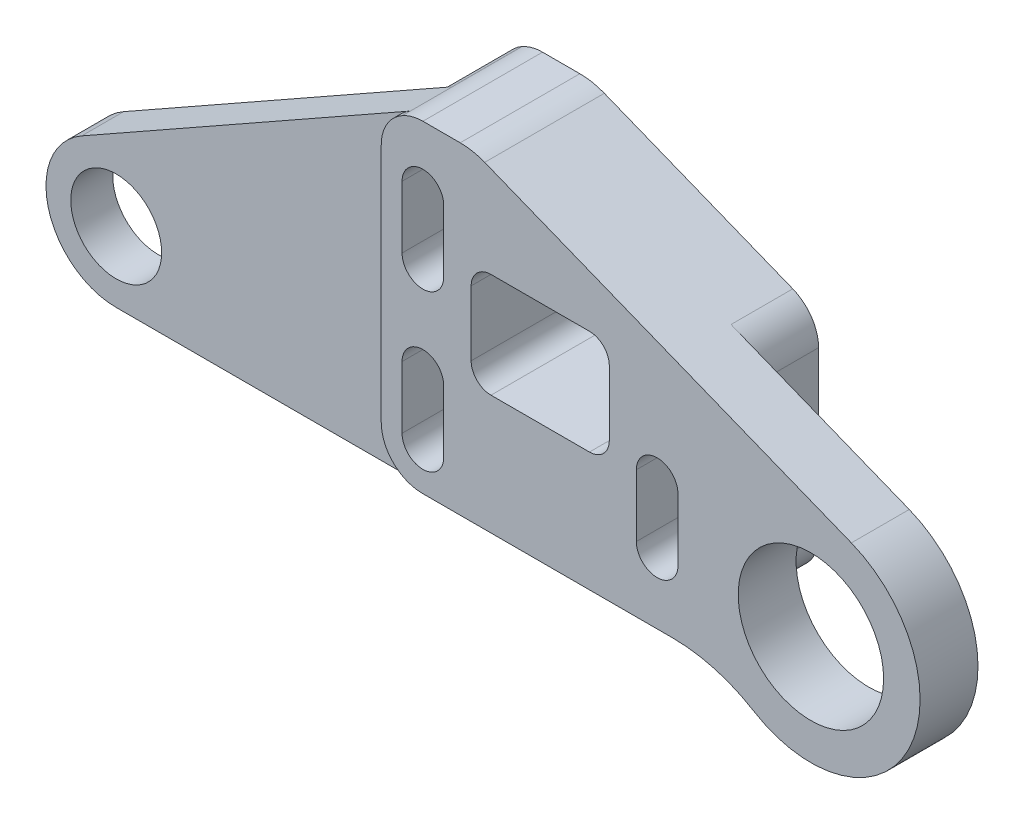
SolidWorks part; units mm, degrees
ref_plane "Plane1" through (0, 0, 0) normal (0, 0, 1) x (1, 0, 0)
ref_plane "Plane2" through (0, 0, 0) normal (0, 1, 0) x (1, 0, 0)
ref_plane "Plane3" through (0, 0, 0) normal (1, 0, 0) x (0, 0, -1)
sketch "Sketch1" plane through (0, 0, 0) normal (0, 0, 1) x (1, 0, 0)
  line L0 (67.6222, 48.4886) -> (60.452, 48.4886)
  line L1 (56.5136, 47.4522) -> (-6.639, 11.7403)
  line L2 (0, -13.4874) -> (108.3963, -13.4874)
  line L3 (142.7734, 19.4876) -> (72.3271, 47.5849)
  arc A0 (-6.639, 11.7403) -> (0, -13.4874) centre (0, 0) ccw
  arc A1 (124.0515, -17.8965) -> (108.3963, -13.4874) centre (108.3963, -43.4848) ccw
  arc A2 (124.0515, -17.8965) -> (142.7734, 19.4876) centre (135.0009, 0.0001) ccw
  arc A3 (72.3271, 47.5849) -> (67.6222, 48.4886) centre (67.6222, 35.7886) ccw
  arc A4 (60.452, 48.4886) -> (56.5136, 47.4522) centre (60.452, 40.4876) ccw
extrude "Base-Extrude" add sketch "Sketch1" along normal blind 22.987
sketch "Sketch2" plane through (0, 0, 22.987) normal (0, 0, 1) x (1, 0, 0)
  line L0 (52.451, 40.5617) -> (52.451, -5.6134)
  line L2 (56.5136, 52.1592) -> (-22.1734, 52.1592)
  line L3 (56.5136, 47.4522) -> (-6.639, 11.7403) construction
  line L4 (56.5136, 47.4522) -> (56.4491, 47.4157)
  line L5 (56.5136, 47.4522) -> (56.5136, 52.1592)
  line L6 (60.325, -13.4874) -> (60.325, -28.1506)
  line L7 (-22.1734, 52.1592) -> (-23.4863, -28.1506)
  line L8 (-23.4863, -28.1506) -> (60.325, -28.1506)
  arc A0 (-6.639, 11.7403) -> (0, -13.4874) centre (0, 0) ccw construction
  arc A1 (60.325, -13.4874) -> (52.451, -5.6134) centre (60.325, -5.6134) cw
  arc A2 (56.4491, 47.4157) -> (52.451, 40.5617) centre (60.325, 40.5617) ccw
  dimension "D2" = 7.874
  dimension "D3" = 7.874
  dimension "D1" = 52.451
extrude "Cut-Extrude1" cut sketch "Sketch2" against normal blind 1.524
sketch "Sketch3" plane through (0, 0, 0) normal (0, 0, -1) x (-1, 0, 0)
  line L0 (-52.451, 40.5617) -> (-52.451, -5.6134) construction
  line L1 (-52.451, 40.5617) -> (-52.451, -5.6134)
  line L2 (-56.4491, 47.4157) -> (-56.4491, 62.4376)
  line L3 (-60.325, -13.4874) -> (-60.325, -35.5857)
  line L4 (-60.325, -35.5857) -> (18.4619, -35.5857)
  line L5 (18.4619, -35.5857) -> (18.4619, 62.4376)
  line L6 (18.4619, 62.4376) -> (-56.4491, 62.4376)
  arc A0 (-60.325, -13.4874) -> (-52.451, -5.6134) centre (-60.325, -5.6134) ccw construction
  arc A1 (-60.325, -13.4874) -> (-52.451, -5.6134) centre (-60.325, -5.6134) ccw
  arc A2 (-52.451, 40.5617) -> (-56.4491, 47.4157) centre (-60.325, 40.5617) ccw construction
  arc A3 (-52.451, 40.5617) -> (-56.4491, 47.4157) centre (-60.325, 40.5617) ccw
extrude "Cut-Extrude2" cut sketch "Sketch3" against normal blind 13.3858
sketch "Sketch4" plane through (0, 0, 0) normal (0, 0, -1) x (-1, 0, 0)
  line L0 (-113.4872, -5.6134) -> (-113.4872, 25.8317)
  line L5 (-108.5303, 33.1454) -> (-119.3461, 60.2632)
  line L6 (-105.6132, -13.4874) -> (-105.6132, -25.7396)
  line L7 (-105.6132, -25.7396) -> (-162.925, -25.7396)
  line L8 (-162.925, -25.7396) -> (-162.925, 60.2632)
  line L9 (-162.925, 60.2632) -> (-119.3461, 60.2632)
  arc A0 (0, -13.4874) -> (6.639, 11.7403) centre (0, 0) ccw construction
  arc A1 (-113.4872, 25.8317) -> (-108.5303, 33.1454) centre (-105.6132, 25.8317) cw
  arc A2 (-105.6132, -13.4874) -> (-113.4872, -5.6134) centre (-105.6132, -5.6134) cw
  dimension "D2" = 7.874
  dimension "D3" = 7.874
  dimension "D1" = 113.4872
extrude "Cut-Extrude3" cut sketch "Sketch4" against normal blind 11.8618
sketch "Sketch5" plane through (0, 0, 21.463) normal (0, 0, 1) x (1, 0, 0)
  circle A0 centre (0, 0) radius 8.7313
  dimension "D1" = 17.4625
extrude "Cut-Extrude4" cut sketch "Sketch5" against normal through all
sketch "Sketch6" plane through (0, 0, 22.987) normal (0, 0, 1) x (1, 0, 0)
  circle A0 centre (135.0009, 0.0001) radius 13.97
  dimension "D1" = 27.94
extrude "Cut-Extrude5" cut sketch "Sketch6" against normal through all
sketch "Sketch7" plane through (0, 0, 22.987) normal (0, 0, 1) x (1, 0, 0)
  line L0 (60.452, 58.42) -> (60.452, -33.02) construction
  line L1 (60.325, -13.4874) -> (108.3963, -13.4874) construction
  line L2 (60.325, -13.4874) -> (0, -13.4874) construction
  line L3 (64.4525, -5.4356) -> (64.4525, 6.5024)
  line L4 (64.4525, 24.5618) -> (64.4525, 36.4998)
  line L5 (56.4515, 36.4998) -> (56.4515, 24.5618)
  line L6 (56.4515, 6.5024) -> (56.4515, -5.4356)
  line L7 (105.4608, 43.18) -> (105.4608, -45.0596) construction
  line L8 (101.4603, 10.9982) -> (101.4603, -0.9398)
  line L9 (73.533, 29.5402) -> (92.456, 29.5402)
  line L10 (69.723, 25.7302) -> (69.723, 13.2588)
  line L11 (92.456, 9.4488) -> (73.533, 9.4488)
  line L12 (96.266, 13.2588) -> (96.266, 25.7302)
  line L13 (109.4613, 10.9982) -> (109.4613, -0.9398)
  circle A0 centre (0, 0) radius 8.7313 construction
  arc A1 (64.4525, 36.4998) -> (56.4515, 36.4998) centre (60.452, 36.4998) ccw
  arc A2 (56.4515, 24.5618) -> (64.4525, 24.5618) centre (60.452, 24.5618) ccw
  arc A3 (64.4525, 6.5024) -> (56.4515, 6.5024) centre (60.452, 6.5024) ccw
  arc A4 (56.4515, -5.4356) -> (64.4525, -5.4356) centre (60.452, -5.4356) ccw
  arc A5 (101.4603, -0.9398) -> (109.4613, -0.9398) centre (105.4608, -0.9398) ccw
  arc A6 (109.4613, 10.9982) -> (101.4603, 10.9982) centre (105.4608, 10.9982) ccw
  arc A7 (69.723, 25.7302) -> (73.533, 29.5402) centre (73.533, 25.7302) cw
  arc A8 (73.533, 9.4488) -> (69.723, 13.2588) centre (73.533, 13.2588) cw
  arc A9 (96.266, 13.2588) -> (92.456, 9.4488) centre (92.456, 13.2588) cw
  arc A10 (92.456, 29.5402) -> (96.266, 25.7302) centre (92.456, 25.7302) cw
  dimension "D2" = 8.001
  dimension "D7" = 105.4608
  dimension "D8" = 69.723
  dimension "D12" = 8.001
  dimension "D13" = 8.001
  dimension "D11" = 3.81
  dimension "D9" = 3.81
  dimension "D16" = 3.81
  dimension "D17" = 3.81
  dimension "D1" = 60.452
  dimension "D3" = 8.0518
  dimension "D4" = 19.9898
  dimension "D5" = 38.0492
  dimension "D6" = 49.9872
  dimension "D10" = 9.4488
  dimension "D14" = 0.9398
  dimension "D15" = 11.938
extrude "Cut-Extrude6" cut sketch "Sketch7" against normal through all
ref_plane "Plane4" through (0, 0, 24.257) normal (0, 0, 1) x (1, 0, 0)
sketch "Stock Profile" plane through (0, 0, 24.257) normal (0, 0, 1) x (1, 0, 0)
  line L0 (-25.4, -38.1) -> (167.64, -38.1)
  line L1 (-25.4, -38.1) -> (-25.4, 58.42)
  line L2 (167.64, 58.42) -> (-25.4, 58.42)
  line L3 (167.64, 58.42) -> (167.64, -38.1)
sketch "Outside Part Profile" plane through (0, 0, 22.987) normal (0, 0, 1) x (1, 0, 0)
  line L3 (0, -13.4874) -> (60.325, -13.4874)
  line L4 (52.451, -5.6134) -> (52.451, 40.5617)
  line L5 (56.5136, 47.4522) -> (56.4491, 47.4157)
  line L6 (52.451, 40.5617) -> (52.451, -5.6134)
  line L7 (60.325, -13.4874) -> (108.3963, -13.4874)
  line L8 (142.7734, 19.4876) -> (72.3271, 47.5849)
  line L9 (67.6222, 48.4886) -> (60.452, 48.4886)
  line L12 (60.325, -13.4874) -> (108.3963, -13.4874)
  line L13 (142.7734, 19.4876) -> (72.3271, 47.5849)
  line L14 (67.6222, 48.4886) -> (60.452, 48.4886)
  line L15 (56.4491, 47.4157) -> (-6.639, 11.7403)
  line L16 (0, -13.4874) -> (60.325, -13.4874)
  line L18 (56.5136, 47.4522) -> (-6.639, 11.7403)
  arc A3 (-6.639, 11.7403) -> (0, -13.4874) centre (0, 0) ccw
  arc A4 (52.451, -5.6134) -> (60.325, -13.4874) centre (60.325, -5.6134) ccw
  arc A5 (56.4491, 47.4157) -> (52.451, 40.5617) centre (60.325, 40.5617) ccw
  arc A6 (56.4491, 47.4157) -> (52.451, 40.5617) centre (60.325, 40.5617) ccw
  arc A7 (52.451, -5.6134) -> (60.325, -13.4874) centre (60.325, -5.6134) ccw
  arc A8 (124.0515, -17.8965) -> (108.3963, -13.4874) centre (108.3963, -43.4848) ccw
  arc A9 (124.0515, -17.8965) -> (142.7734, 19.4876) centre (135.0009, 0.0001) ccw
  arc A10 (72.3271, 47.5849) -> (67.6222, 48.4886) centre (67.6222, 35.7886) ccw
  arc A11 (60.452, 48.4886) -> (56.5136, 47.4522) centre (60.452, 40.4876) ccw
  arc A14 (124.0515, -17.8965) -> (108.3963, -13.4874) centre (108.3963, -43.4848) ccw
  arc A15 (124.0515, -17.8965) -> (142.7734, 19.4876) centre (135.0009, 0.0001) ccw
  arc A16 (72.3271, 47.5849) -> (67.6222, 48.4886) centre (67.6222, 35.7886) ccw
  arc A17 (60.452, 48.4886) -> (56.5136, 47.4522) centre (60.452, 40.4876) ccw
  arc A18 (-6.639, 11.7403) -> (0, -13.4874) centre (0, 0) ccw
  dimension "D1" = 0
  dimension "D2" = 0
sketch "Setup Origin" plane through (0, 0, 24.257) normal (0, 0, 1) x (1, 0, 0)
  circle A0 centre (-25.4, -38.1) radius 5.1104
